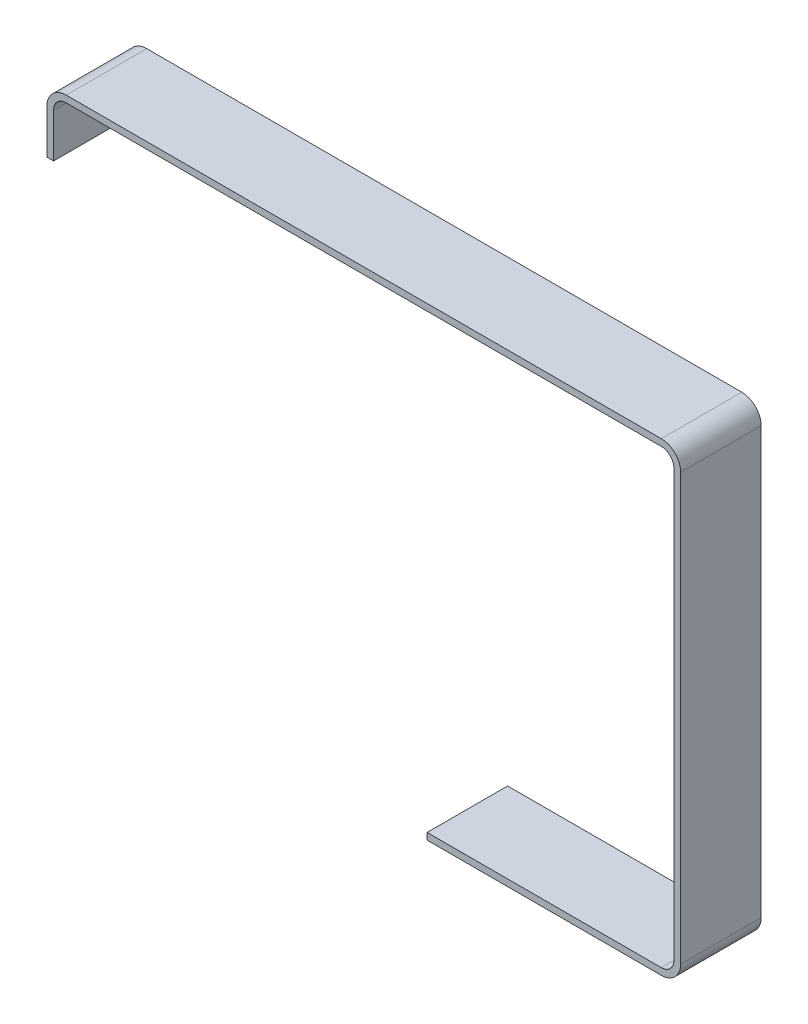
SolidWorks part; units mm, degrees
ref_plane "Front Plane" through (0, 0, 0) normal (0, 0, 1) x (1, 0, 0)
ref_plane "Top Plane" through (0, 0, 0) normal (0, 1, 0) x (1, 0, 0)
ref_plane "Right Plane" through (0, 0, 0) normal (1, 0, 0) x (0, 0, -1)
sketch "Sketch1" plane through (0, 0, 0) normal (0, 0, 1) x (1, 0, 0)
  line L0 (-60, 0) -> (0, 0)
  line L1 (0, 0) -> (0, 110)
  line L2 (0, 110) -> (-150, 110)
  line L3 (-150, 110) -> (-150, 95)
  line L4 (-60, 1.5875) -> (-1.5875, 1.5875)
  line L5 (-1.5875, 1.5875) -> (-1.5875, 108.4125)
  line L6 (-1.5875, 108.4125) -> (-148.4125, 108.4125)
  line L7 (-148.4125, 108.4125) -> (-148.4125, 95)
  line L8 (-150, 95) -> (-148.4125, 95)
  line L9 (-60, 0) -> (-60, 1.5875)
  dimension "D1" = 60
  dimension "D2" = 110
  dimension "D3" = 150
  dimension "D4" = 15
  dimension "D5" = 1.5875
extrude "Boss-Extrude1" add sketch "Sketch1" along normal blind 19.05
fillet "Fillet1" radius 3 3 edges at (-1.5875, 1.5875, 9.525) (-1.5875, 108.4125, 9.525) (-148.4125, 108.4125, 9.525)
fillet "Fillet2" radius 4.5875 3 edges at (0, 0, 9.525) (0, 110, 9.525) (-150, 110, 9.525)
